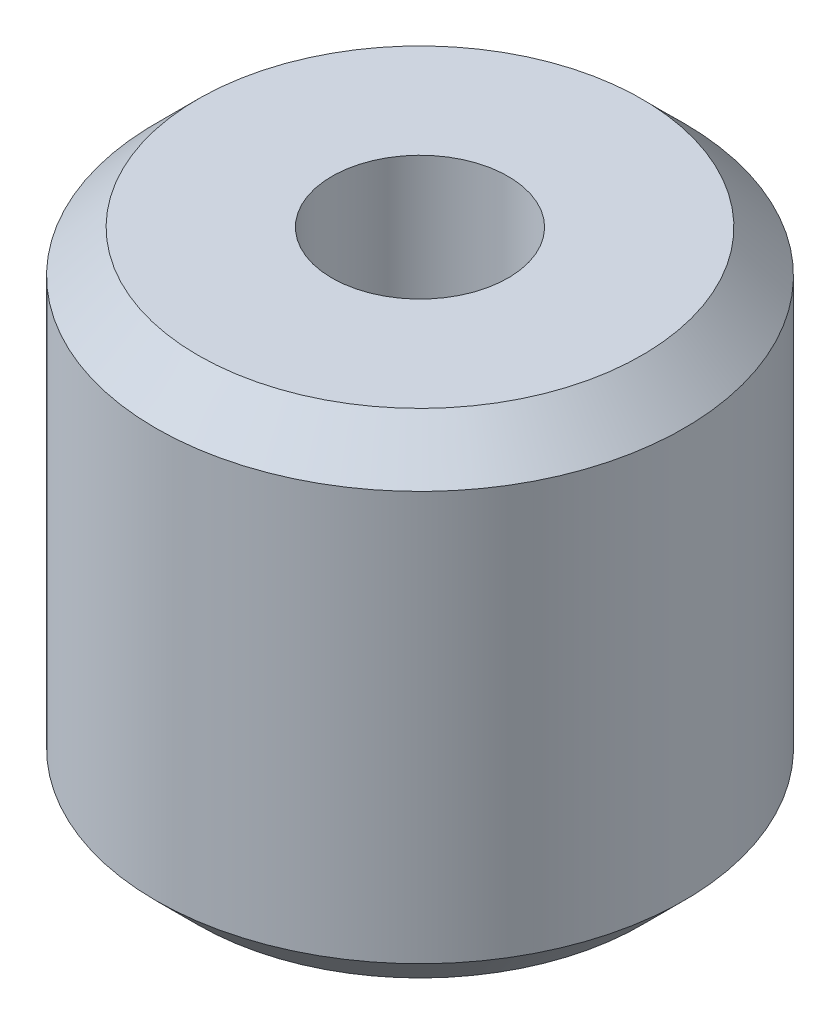
SolidWorks part; units mm, degrees
ref_plane "Front Plane" through (0, 0, 0) normal (0, 0, 1) x (1, 0, 0)
ref_plane "Top Plane" through (0, 0, 0) normal (0, 1, 0) x (1, 0, 0)
ref_plane "Right Plane" through (0, 0, 0) normal (1, 0, 0) x (0, 0, -1)
sketch "Sketch1" plane through (0, 0, 0) normal (0, 1, 0) x (1, 0, 0)
  circle A0 centre (0, 0) radius 4.765
  circle A1 centre (0, 0) radius 1.59
  dimension "D1" = 9.53
  dimension "D2" = 3.18
extrude "Boss-Extrude1" add sketch "Sketch1" along normal blind 8.9
chamfer "Chamfer1" distance 0.76 angle 45 1 edges at (0, 8.9, 4.765)
chamfer "Chamfer2" distance 0.76 angle 45 1 edges at (0, 0, 4.765)
